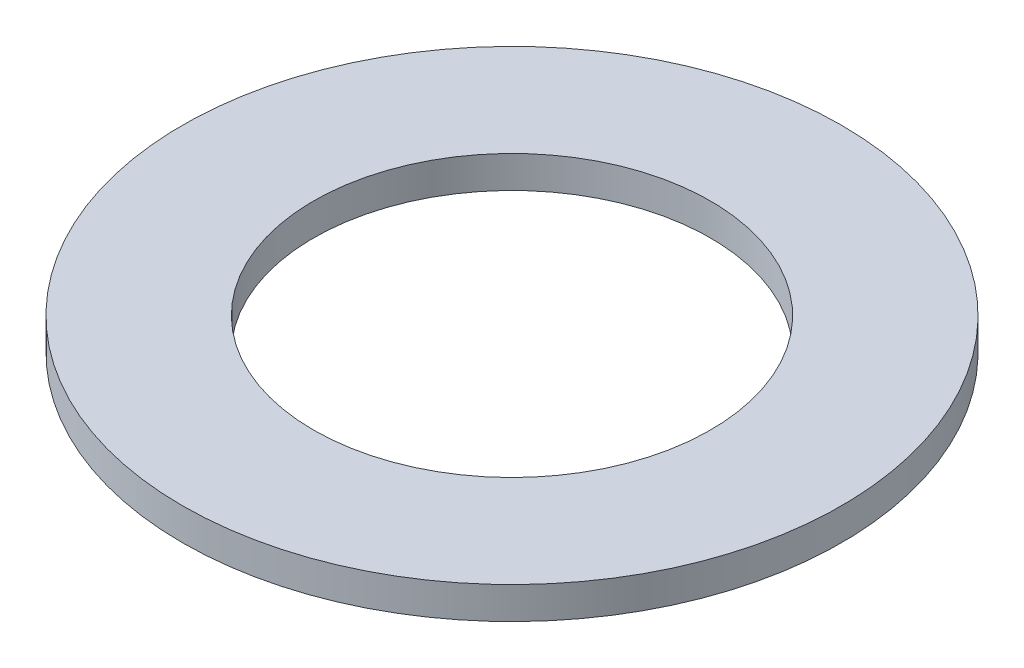
SolidWorks part; units mm, degrees
ref_plane "Front Plane" through (0, 0, 0) normal (0, 0, 1) x (1, 0, 0)
ref_plane "Top Plane" through (0, 0, 0) normal (0, 1, 0) x (1, 0, 0)
ref_plane "Right Plane" through (0, 0, 0) normal (1, 0, 0) x (0, 0, -1)
sketch "Sketch1" plane through (0, 0, 0) normal (0, 1, 0) x (1, 0, 0)
  circle A0 centre (0, 0) radius 82.2
  circle A1 centre (0, 0) radius 49.5
  dimension "D1" = 164.4
  dimension "D2" = 99
extrude "Boss-Extrude1" add sketch "Sketch1" along normal blind 8
